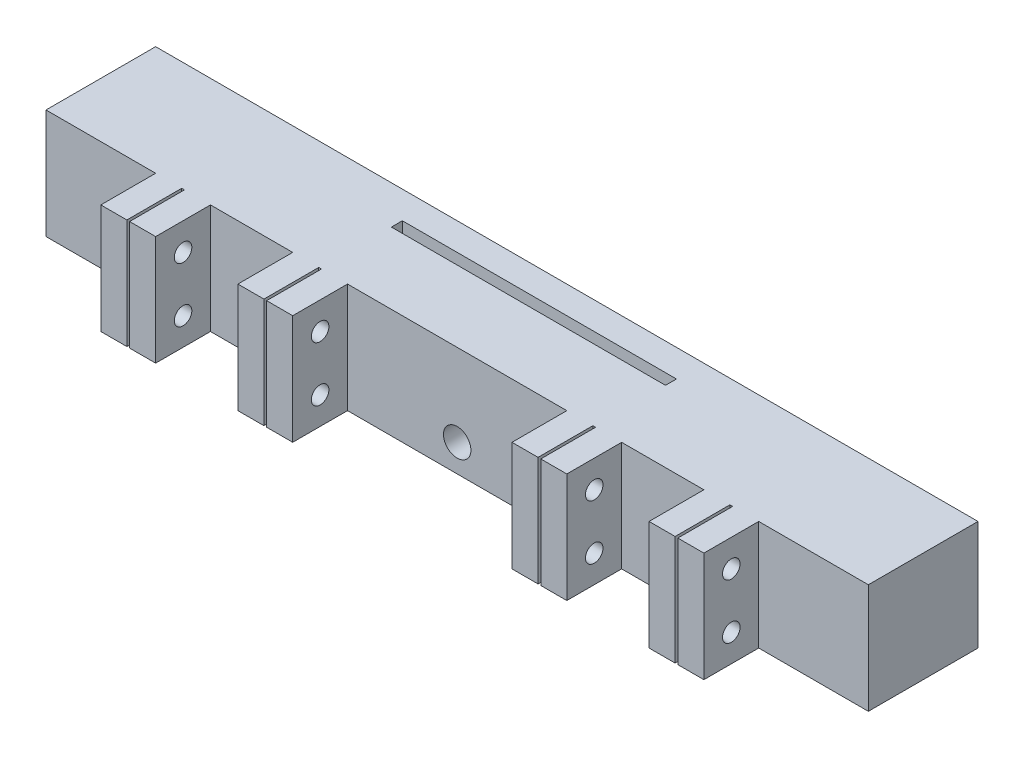
SolidWorks part; units mm, degrees
ref_plane "Front Plane" through (0, 0, 0) normal (0, 0, 1) x (1, 0, 0)
ref_plane "Top Plane" through (0, 0, 0) normal (0, 1, 0) x (1, 0, 0)
ref_plane "Right Plane" through (0, 0, 0) normal (1, 0, 0) x (0, 0, -1)
sketch "Sketch1" plane through (0, 0, 0) normal (0, 1, 0) x (1, 0, 0)
  line L0 (0, 0) -> (-75, 0)
  line L2 (-55, -30) -> (-45, -30)
  line L3 (-45, -30) -> (-45, -20)
  line L4 (-45, -20) -> (-30, -20)
  line L5 (-30, -20) -> (-30, -30)
  line L6 (-30, -30) -> (-20, -30)
  line L7 (-20, -30) -> (-20, -20)
  line L10 (20, -20) -> (20, -30)
  line L11 (20, -30) -> (30, -30)
  line L12 (30, -30) -> (30, -20)
  line L13 (30, -20) -> (45, -20)
  line L14 (45, -20) -> (45, -30)
  line L15 (45, -30) -> (55, -30)
  line L17 (75, 0) -> (0, 0)
  line L18 (-20, -20) -> (20, -20)
  line L19 (-75, 0) -> (-75, -20)
  line L20 (-75, -20) -> (-55, -20)
  line L21 (-55, -20) -> (-55, -30)
  line L22 (55, -30) -> (55, -20)
  line L23 (55, -20) -> (75, -20)
  line L24 (75, -20) -> (75, 0)
  line L25 (0, 0) -> (0, -20) construction
  point P3 (-25, -30)
  point P11 (-50, -30)
  dimension "D1" = 50
  dimension "D2" = 20
  dimension "D3" = 10
  dimension "D4" = 10
  dimension "D5" = 25
  dimension "D6" = 150
extrude "Boss-Extrude1" add sketch "Sketch1" along normal blind 20
sketch "Sketch2" plane through (0, 20, 0) normal (0, 1, 0) x (1, 0, 0)
  line L0 (-55, -30) -> (-45, -30) construction
  line L1 (-49.75, -30) -> (-50.25, -30)
  line L2 (-49.75, -30) -> (-49.75, -20)
  line L3 (-49.75, -20) -> (-50.25, -20)
  line L4 (-50.25, -30) -> (-50.25, -20)
  line L5 (-30, -30) -> (-20, -30) construction
  line L6 (-24.75, -30) -> (-25.25, -30)
  line L7 (-24.75, -30) -> (-24.75, -20)
  line L8 (-24.75, -20) -> (-25.25, -20)
  line L9 (-25.25, -30) -> (-25.25, -20)
  line L10 (20, -30) -> (30, -30) construction
  line L11 (24.75, -30) -> (25.25, -30)
  line L12 (24.75, -30) -> (24.75, -20)
  line L13 (24.75, -20) -> (25.25, -20)
  line L14 (25.25, -30) -> (25.25, -20)
  line L15 (45, -30) -> (55, -30) construction
  line L16 (50.25, -30) -> (49.75, -30)
  line L17 (50.25, -30) -> (50.25, -20)
  line L18 (50.25, -20) -> (49.75, -20)
  line L19 (49.75, -30) -> (49.75, -20)
  line L20 (55, -20) -> (75, -20) construction
  line L21 (30, -20) -> (45, -20) construction
  point P24 (50, -30)
  point P25 (50, -30)
  point P30 (25, -30)
  point P31 (25, -30)
  point P32 (-25, -30)
  point P33 (-25, -30)
  point P34 (-50, -30)
  point P35 (-50, -30)
  dimension "D1" = 0.5
extrude "Cut-Extrude1" cut sketch "Sketch2" against normal through all both and the other way through all
sketch "Sketch3" plane through (-55, 0, 0) normal (-1, 0, 0) x (0, 0, 1)
  line L0 (25, 20) -> (25, 15) construction
  line L1 (20, 20) -> (30, 20) construction
  line L2 (30, 10) -> (20, 10) construction
  line L4 (30, 20) -> (30, 0) construction
  line L5 (20, 20) -> (20, 0) construction
  circle A0 centre (25, 15) radius 1.6
  circle A1 centre (25, 5) radius 1.6
  point P13 (25.1813, 5.7866)
  point P14 (25, 14.1559)
  dimension "D1" = 3.2
  dimension "D2" = 10
extrude "Cut-Extrude2" cut sketch "Sketch3" against normal through all both and the other way through all
sketch "Sketch4" plane through (0, 20, 0) normal (0, 1, 0) x (1, 0, 0)
  line L0 (0, 0) -> (0, -5) construction
  line L1 (-25, -5) -> (25, -5)
  line L2 (-25, -5) -> (-25, -7)
  line L3 (-25, -7) -> (25, -7)
  line L4 (25, -5) -> (25, -7)
  line L5 (75, 0) -> (-75, 0) construction
  dimension "D1" = 2
  dimension "D2" = 5
  dimension "D3" = 50
extrude "Cut-Extrude3" cut sketch "Sketch4" against normal through all both and the other way through all
sketch "Sketch5" plane through (0, 0, 20) normal (0, 0, 1) x (1, 0, 0)
  line L0 (0, 0) -> (0, 5) construction
  circle A0 centre (0, 5) radius 2.5
  dimension "D1" = 5
  dimension "D2" = 5
extrude "Cut-Extrude4" cut sketch "Sketch5" against normal blind 10
